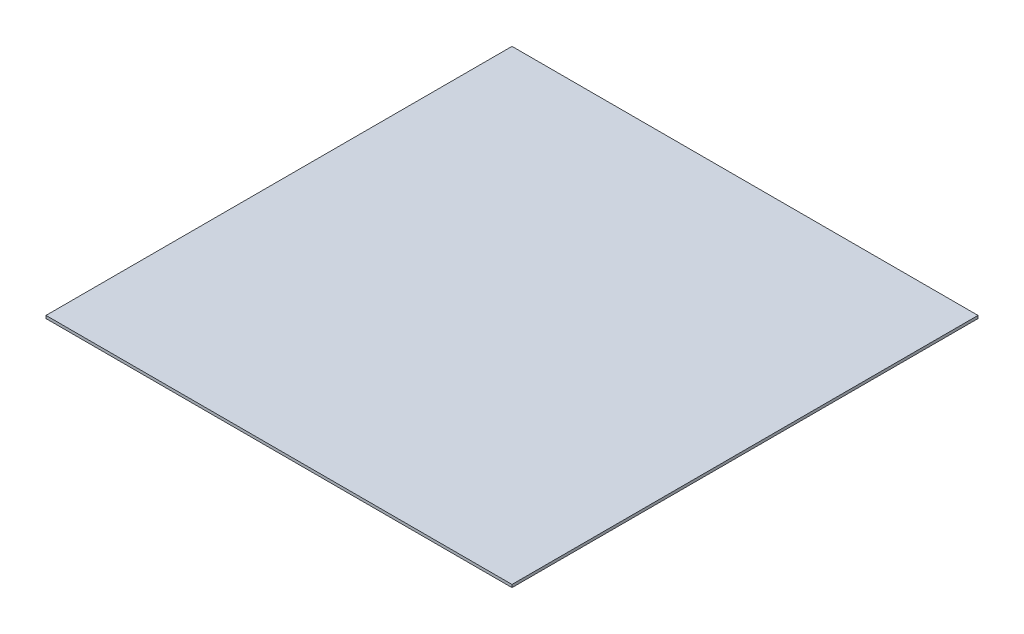
SolidWorks part; units mm, degrees
ref_plane "Спереди" through (0, 0, 0) normal (0, 0, 1) x (1, 0, 0)
ref_plane "Сверху" through (0, 0, 0) normal (0, 1, 0) x (1, 0, 0)
ref_plane "Справа" through (0, 0, 0) normal (1, 0, 0) x (0, 0, -1)
sketch "Эскиз1" plane through (0, 0, 0) normal (0, 1, 0) x (1, 0, 0)
  line L1 (-250, -250) -> (250, -250)
  line L2 (-250, -250) -> (-250, 250)
  line L3 (-250, 250) -> (250, 250)
  line L4 (250, -250) -> (250, 250)
  line L5 (0, 250) -> (0, -250) construction
  line L6 (-250, 0) -> (250, 0) construction
  point P0 (0, 0)
  dimension "D1" = 500
  dimension "D2" = 500
extrude "Бобышка-Вытянуть1" add sketch "Эскиз1" along normal blind 3
